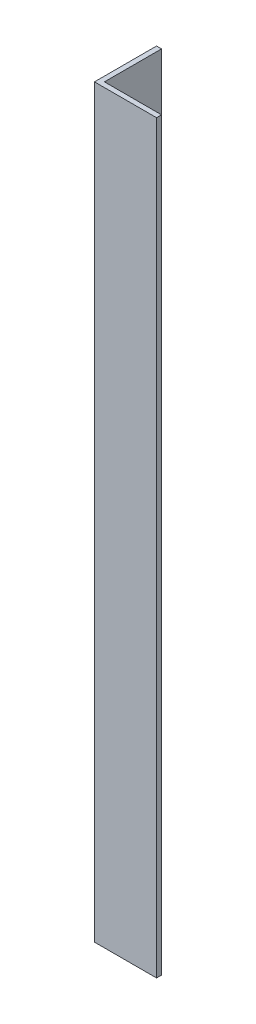
SolidWorks part; units mm, degrees
material "AISI 316 Отожженная нержавеющая сталь. полоса (SS)"
ref_plane "Спереди XY" through (0, 0, 0) normal (0, 0, 1) x (1, 0, 0)
ref_plane "Сверху XZ" through (0, 0, 0) normal (0, 1, 0) x (1, 0, 0)
ref_plane "Справа ZY" through (0, 0, 0) normal (1, 0, 0) x (0, 0, -1)
sketch "Эскиз2" plane through (0, 0, 0) normal (0, 1, 0) x (1, 0, 0)
  line L0 (0, 46) -> (0, 0)
  line L1 (0, 0) -> (46, 0)
  line L2 (-4, 46) -> (-4, -4)
  line L3 (-4, -4) -> (46, -4)
  line L4 (-4, 46) -> (0, 46)
  line L5 (46, 0) -> (46, -4)
  line L6 (0, 46) -> (0, -3.4031) construction
  arc A2 (0, -3.4031) -> (0, 0) centre (4.7015, -1.7016) ccw construction
  circle A3 centre (4.7015, -1.7016) radius 9 construction
  dimension "D2" = 50
  dimension "D3" = 50
  dimension "D1" = 4
extrude "Бобышка-Вытянуть1" add sketch "Эскиз2" along normal blind 600
